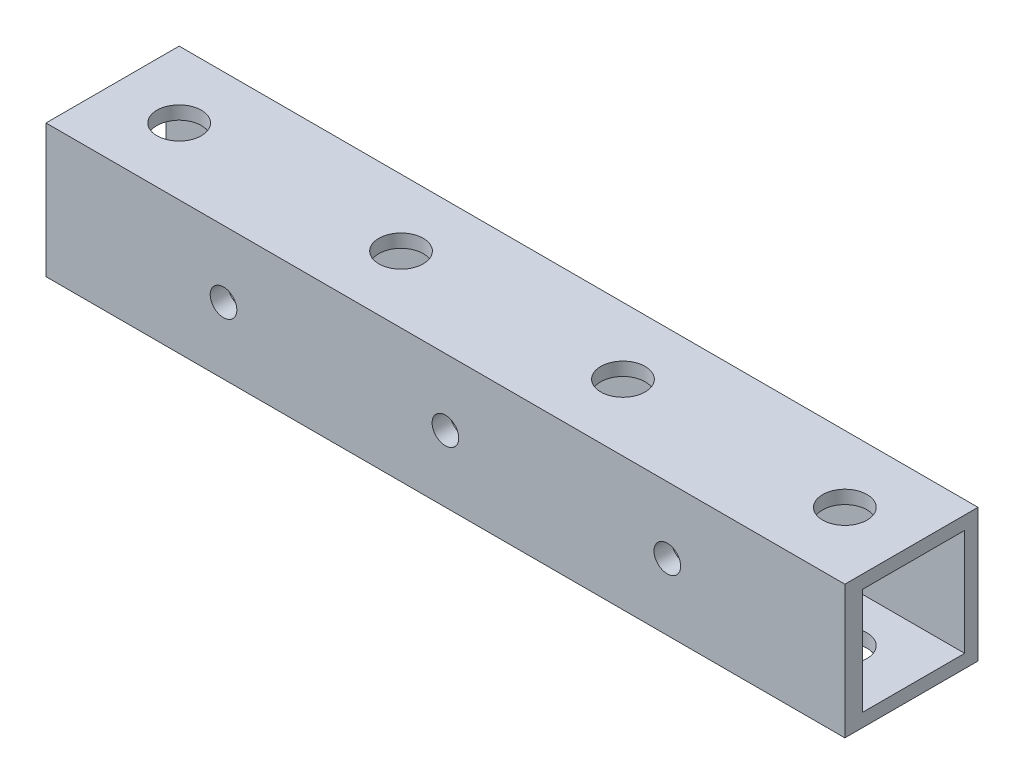
SolidWorks part; units mm, degrees
material "6061 合金"
ref_plane "前视基准面" through (0, 0, 0) normal (0, 0, 1) x (1, 0, 0)
ref_plane "上视基准面" through (0, 0, 0) normal (0, 1, 0) x (1, 0, 0)
ref_plane "右视基准面" through (0, 0, 0) normal (1, 0, 0) x (0, 0, -1)
sketch3d "3D草图1"
  line L0 (0, 0, 0) -> (90, 0, 0)
  dimension "D1" = 90
other "方形管 15 ×15× 1.5(1)"
ref_plane "基准面1" through (0, 0, 0) normal (1, 0, 0) x (0, 0, -1)
sketch "Sketch1" plane through (0, 0, 0) normal (1, 0, 0) x (0, 0, -1)
  line L0 (-4, -6) -> (4, -6)
  line L1 (-5.5, -3.5) -> (-5.5, 3.5)
  line L2 (3.5, 6) -> (-3.5, 6)
  line L3 (6, 3.5) -> (6, -3.5)
  line L4 (-6, -7.5) -> (6, -7.5)
  line L5 (-7.5, -6) -> (-7.5, 6)
  line L6 (6, 7.5) -> (-6, 7.5)
  line L7 (7.5, 6) -> (7.5, -6)
  line L8 (-5.5, 3.5) -> (-5.5, 6)
  line L9 (-5.5, 6) -> (-3.5, 6)
  line L10 (-7.5, 6) -> (-7.5, 7.5)
  line L11 (-7.5, 7.5) -> (-6, 7.5)
  line L12 (6, 7.5) -> (7.5, 7.5)
  line L13 (7.5, 7.5) -> (7.5, 6)
  line L14 (3.5, 6) -> (6, 6)
  line L15 (6, 6) -> (6, 3.5)
  line L16 (4, -6) -> (6, -6)
  line L17 (6, -6) -> (6, -3.5)
  line L18 (7.5, -6) -> (7.5, -7.5)
  line L19 (7.5, -7.5) -> (6, -7.5)
  line L20 (-5.5, -3.5) -> (-5.5, -6)
  line L21 (-5.5, -6) -> (-4, -6)
  line L22 (-7.5, -6) -> (-7.5, -7.5)
  line L23 (-7.5, -7.5) -> (-6, -7.5)
  line L24 (0, 7.5) -> (0, -7.5) construction
  line L25 (-7.5, 0) -> (7.5, 0) construction
  point P0 (-7.5, 0)
  point P1 (7.5, 0)
  point P2 (0, 7.5)
  point P3 (0, -7.5)
  point P4 (0, 0)
  point P5 (-7.5, -7.5)
  point P6 (7.5, -7.5)
  point P7 (7.5, 7.5)
  point P8 (-7.5, 7.5)
  point P38 (6, 0)
  point P39 (-5.5, 0)
  point P40 (0, 6)
  point P41 (0, -6)
  point P42 (0, 0)
  dimension "D1" = 1.5
  dimension "D2" = 1.5
  dimension "D3" = 1.5
  dimension "D4" = 1.5
  dimension "D5" = 1.5
  dimension "D6" = 12
  dimension "D7" = 1.5
  dimension "D8" = 1.5
  dimension "Thickness" = 2
  dimension "D9" = 1.5
  dimension "D10" = 1.5
sketch "草图3" plane through (0, 7.5, 0) normal (0, 1, 0) x (1, 0, 0)
  line L0 (0, 0) -> (90, 0) construction
  line L1 (0, 7.5) -> (0, -7.5) construction
  line L2 (90, 7.5) -> (90, -7.5) construction
  line L3 (90, 7.5) -> (0, 7.5) construction
  line L4 (45, 7.5) -> (45, -7.5) construction
  line L5 (90, -7.5) -> (0, -7.5) construction
  circle A0 centre (7.5, 0) radius 2.5
  circle A1 centre (32.5, 0) radius 2.5
  circle A2 centre (57.5, 0) radius 2.5
  circle A3 centre (82.5, 0) radius 2.5
  dimension "D2" = 25
  dimension "D4" = 5
  dimension "D1" = 7.5
  dimension "D3" = 7.5
extrude "切除-拉伸1" cut sketch "草图3" against normal through all
sketch "草图4" plane through (0, 0, 7.5) normal (0, 0, 1) x (1, 0, 0)
  line L0 (45, 7.5) -> (45, -7.5) construction
  line L1 (90, 7.5) -> (0, 7.5) construction
  line L2 (90, -7.5) -> (0, -7.5) construction
  line L3 (45, 0) -> (20, 0) construction
  circle A0 centre (45, 0) radius 1.5
  circle A1 centre (20, 0) radius 1.5
  circle A2 centre (70, 0) radius 1.5
  dimension "D1" = 25
  dimension "D2" = 3
  dimension "D3" = 3
extrude "切除-拉伸2" cut sketch "草图4" against normal through all
